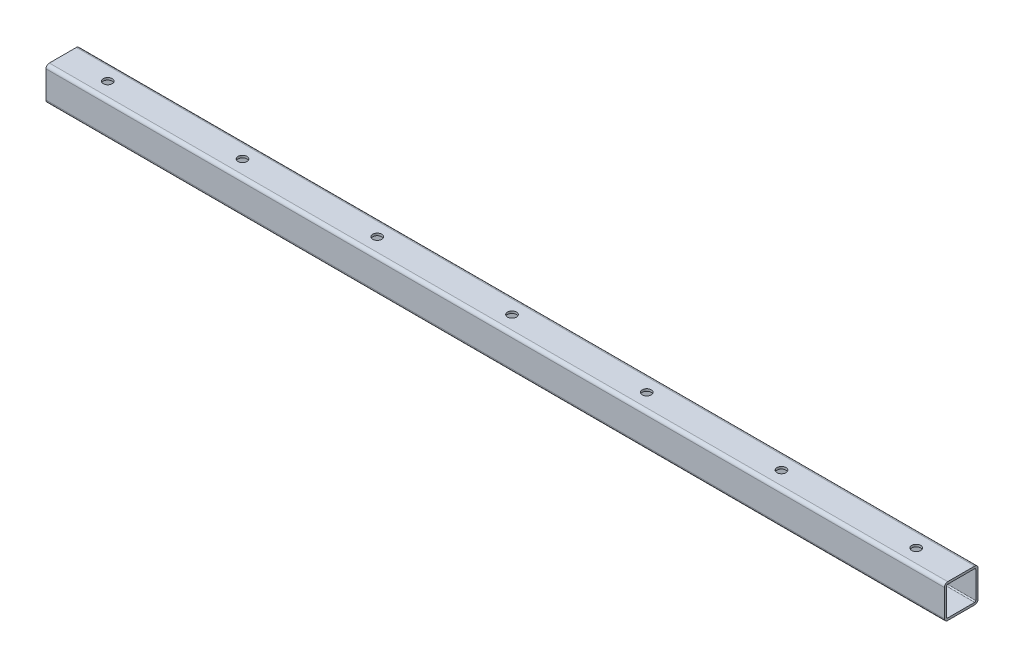
SolidWorks part; units mm, degrees
material "Thornel Mat VMA"
ref_plane "前视基准面" through (0, 0, 0) normal (0, 0, 1) x (1, 0, 0)
ref_plane "上视基准面" through (0, 0, 0) normal (0, 1, 0) x (1, 0, 0)
ref_plane "右视基准面" through (0, 0, 0) normal (1, 0, 0) x (0, 0, -1)
sketch "草图1" plane through (0, 0, 0) normal (1, 0, 0) x (0, 0, -1)
  line L0 (0, 7.5) -> (0, -7.5) construction
  line L1 (6, 7.5) -> (-6, 7.5)
  line L2 (7.5, 6) -> (7.5, -6)
  line L3 (6, -7.5) -> (-6, -7.5)
  line L4 (-7.5, 6) -> (-7.5, -6)
  line L5 (7.5, 0) -> (-7.5, 0) construction
  line L6 (6, 6.5) -> (-6, 6.5)
  line L7 (-6.5, 6) -> (-6.5, -6)
  line L8 (6, -6.5) -> (-6, -6.5)
  line L9 (6.5, 6) -> (6.5, -6)
  arc A0 (7.5, -6) -> (6, -7.5) centre (6, -6) cw
  arc A1 (-6, -7.5) -> (-7.5, -6) centre (-6, -6) cw
  arc A2 (-6, 7.5) -> (-7.5, 6) centre (-6, 6) ccw
  arc A3 (6, 7.5) -> (7.5, 6) centre (6, 6) cw
  arc A4 (-6, 6.5) -> (-6.5, 6) centre (-6, 6) ccw
  arc A5 (-6, -6.5) -> (-6.5, -6) centre (-6, -6) cw
  arc A6 (6.5, -6) -> (6, -6.5) centre (6, -6) cw
  arc A7 (6, 6.5) -> (6.5, 6) centre (6, 6) cw
  point P13 (-7.5, -7.5)
  point P16 (-7.5, 7.5)
  dimension "D2" = 1.5
  dimension "D1" = 15
  dimension "D3" = 1
extrude "凸台-拉伸1" add sketch "草图1" along normal mid plane 400
sketch "草图2" plane through (0, 0, 0) normal (0, 1, 0) x (1, 0, 0)
  line L0 (-200, 6) -> (-200, -6) construction
  line L1 (-180, 0) -> (-120, 0) construction
  circle A0 centre (-180, 0) radius 2
  circle A1 centre (-120, 0) radius 2
  circle A2 centre (-60, 0) radius 2
  circle A3 centre (0, 0) radius 2
  circle A4 centre (60, 0) radius 2
  circle A5 centre (120, 0) radius 2
  circle A6 centre (180, 0) radius 2
  dimension "D2" = 4
  dimension "D1" = 20
  dimension "D4" = 60
  dimension "D3" = 7
extrude "切除-拉伸1" cut sketch "草图2" against normal through all both and the other way through all
